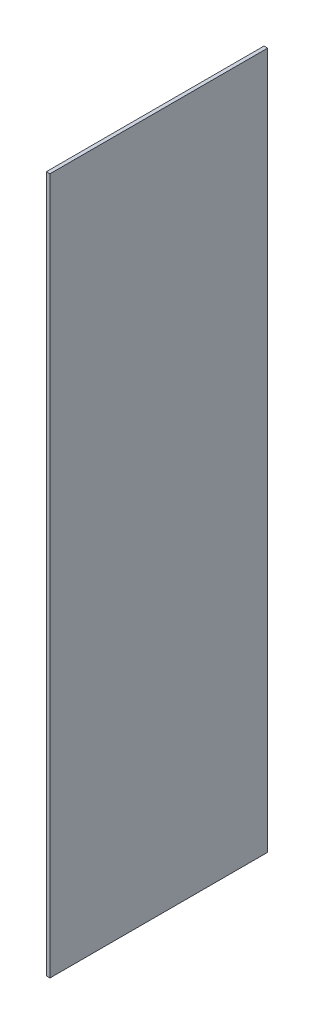
SolidWorks part; units mm, degrees
ref_plane "Front Plane" through (0, 0, 0) normal (0, 0, 1) x (1, 0, 0)
ref_plane "Top Plane" through (0, 0, 0) normal (0, 1, 0) x (1, 0, 0)
ref_plane "Right Plane" through (0, 0, 0) normal (1, 0, 0) x (0, 0, -1)
sketch "Sketch2" plane through (0, 0, 0) normal (0, 1, 0) x (1, 0, 0)
  line L1 (-6.35, -381) -> (6.35, -381)
  line L2 (-6.35, -381) -> (-6.35, 381)
  line L3 (-6.35, 381) -> (6.35, 381)
  line L4 (6.35, -381) -> (6.35, 381)
  line L5 (-6.35, -381) -> (6.35, 381) construction
  line L6 (-6.35, 381) -> (6.35, -381) construction
  point P0 (0, 0)
extrude "Boss-Extrude1" add sketch "Sketch2" along normal blind 2438.4
